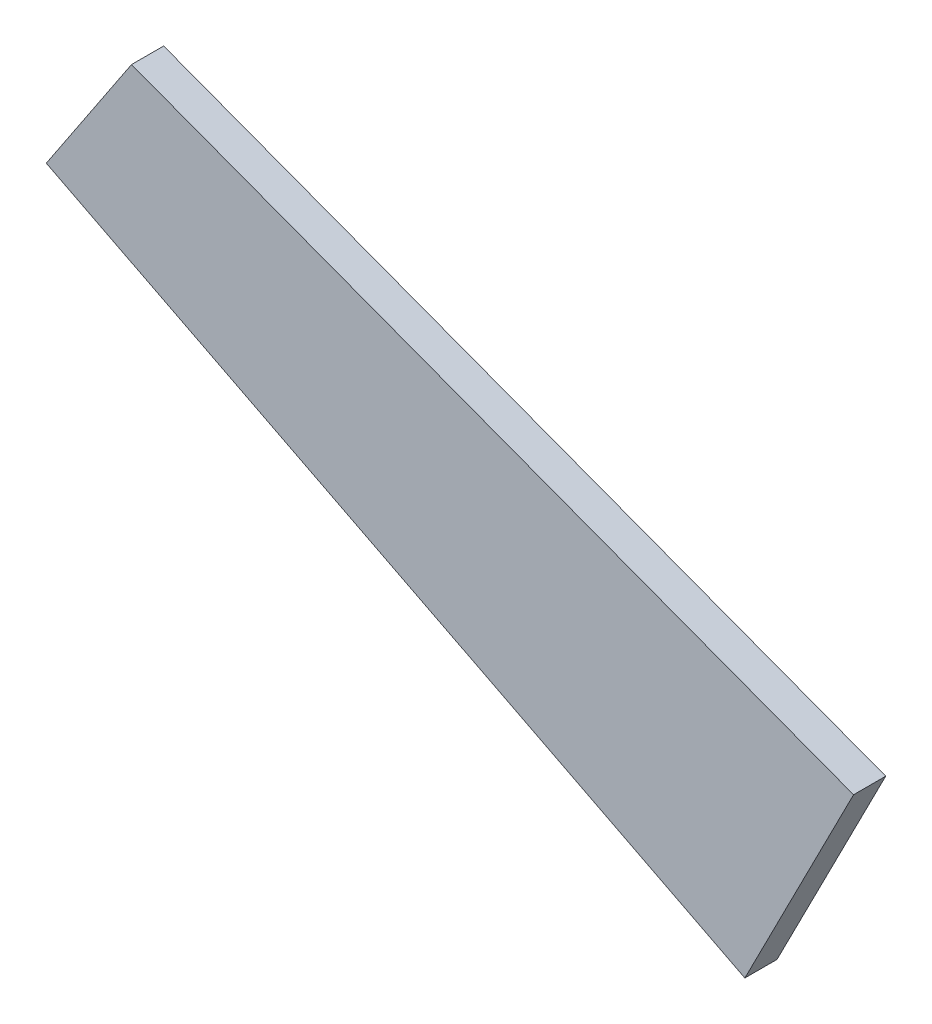
SolidWorks part; units mm, degrees
material "Plain Carbon Steel"
ref_plane "Front Plane" through (0, 0, 0) normal (0, 0, 1) x (1, 0, 0)
ref_plane "Top Plane" through (0, 0, 0) normal (0, 1, 0) x (1, 0, 0)
ref_plane "Right Plane" through (0, 0, 0) normal (1, 0, 0) x (0, 0, -1)
sketch "Sketch1" plane through (0, 0, 0) normal (0, 0, 1) x (1, 0, 0)
  line L0 (259.8085, 74.7833) -> (253.0711, 64.6628)
  line L1 (253.0711, 64.6628) -> (308.2995, 36.4883)
  line L2 (308.2995, 36.4883) -> (316.8922, 53.332)
  line L3 (316.8922, 53.332) -> (259.8085, 74.7833)
ref_plane "Plane1" through (-38.3438, 15.5822, -33.02) normal (0.4056, 0.9141, 0) x (-0.9141, 0.4056, 0)
extrude "Boss-Extrude1" add sketch "Sketch1" along normal blind 2.54
sketch "Sketch2" plane through (0, 0, 0) normal (0, 0, -1) x (-1, 0, 0)
  circle A0 centre (-292.2793, 42.6353) radius 0.7938
